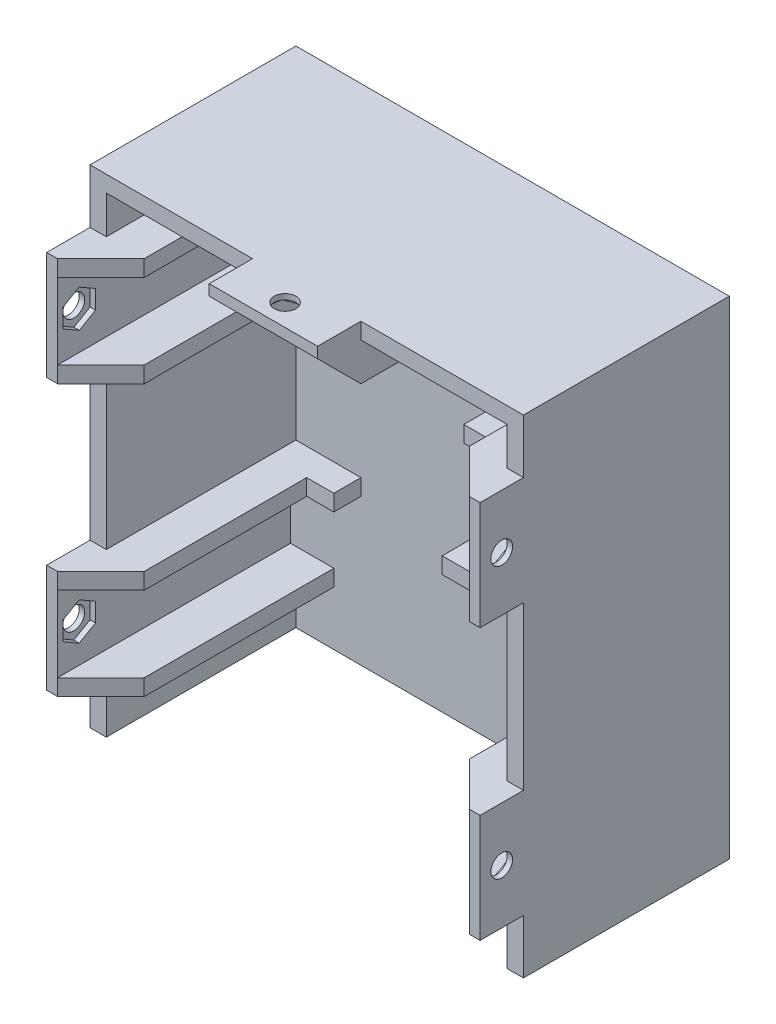
SolidWorks part; units mm, degrees
ref_plane "Front Plane" through (0, 0, 0) normal (0, 0, 1) x (1, 0, 0)
ref_plane "Top Plane" through (0, 0, 0) normal (0, 1, 0) x (1, 0, 0)
ref_plane "Right Plane" through (0, 0, 0) normal (1, 0, 0) x (0, 0, -1)
sketch "Sketch1" plane through (0, 0, 0) normal (0, 0, 1) x (1, 0, 0)
  line L1 (0, 0) -> (80, 0)
  line L2 (0, 0) -> (0, 90)
  line L3 (0, 90) -> (80, 90)
  line L4 (80, 0) -> (80, 90)
  dimension "D1" = 90
  dimension "D2" = 80
extrude "Boss-Extrude1" add sketch "Sketch1" along normal blind 3
sketch "Sketch2" plane through (0, 0, 3) normal (0, 0, 1) x (1, 0, 0)
  line L0 (0, 90) -> (0, 0) construction
  line L1 (0, 80) -> (10, 80)
  line L2 (0, 80) -> (0, 60)
  line L3 (0, 60) -> (10, 60)
  line L4 (10, 80) -> (10, 77)
  line L5 (80, 90) -> (0, 90) construction
  line L6 (10, 77) -> (2, 77)
  line L7 (2, 77) -> (2, 63)
  line L8 (2, 63) -> (10, 63)
  line L9 (10, 63) -> (10, 60)
  dimension "D1" = 10
  dimension "D2" = 20
  dimension "D3" = 3
  dimension "D4" = 3
  dimension "D5" = 2
  dimension "D6" = 10
extrude "Boss-Extrude2" add sketch "Sketch2" along normal blind 8
sketch "Sketch3" plane through (0, 80, 0) normal (0, 1, 0) x (1, 0, 0)
  line L0 (10, -3) -> (2, -11)
  line L1 (10, -11) -> (0, -11) construction
  line L2 (2, -11) -> (10, -11)
  line L3 (10, -11) -> (10, -3)
  line L4 (10, -3) -> (0, -3) construction
  dimension "D1" = 45
extrude "Cut-Extrude1" cut sketch "Sketch3" against normal through all
sketch "Sketch6" plane through (2, 0, 0) normal (1, 0, 0) x (0, 0, -1)
  line L0 (-11, 63) -> (-11, 77) construction
  line L1 (-11, 80) -> (-3, 80) construction
  circle A0 centre (-7, 70) radius 2
  dimension "D1" = 4
  dimension "D2" = 10
extrude "Cut-Extrude3" cut sketch "Sketch6" against normal blind 25
ref_plane "Plane1" through (40, 0, 0) normal (1, 0, 0) x (0, 0, -1)
ref_plane "Plane3" through (0, 45, 0) normal (0, -1, 0) x (-1, 0, 0)
mirror "Mirror4" about plane through (40, 0, 0) normal (1, 0, 0) of "Cut-Extrude3", "Boss-Extrude2", "Cut-Extrude1"
mirror "Mirror5" about plane through (0, 45, 0) normal (0, -1, 0) of "Boss-Extrude2", "Cut-Extrude1", "Mirror4", "Cut-Extrude3"
sketch "Sketch4" plane through (0, 0, 3) normal (0, 0, 1) x (1, 0, 0)
  line L0 (80, 90) -> (0, 90) construction
  line L1 (30, 90) -> (50, 90)
  line L2 (30, 90) -> (30, 80)
  line L3 (30, 80) -> (33, 80)
  line L4 (50, 90) -> (50, 80)
  line L5 (40, -1.65) -> (40, 1.65) construction
  line L6 (33, 80) -> (33, 88)
  line L7 (33, 88) -> (47, 88)
  line L8 (47, 88) -> (47, 80)
  line L9 (47, 80) -> (50, 80)
  dimension "D1" = 20
  dimension "D2" = 10
  dimension "D3" = 10
  dimension "D4" = 3
  dimension "D5" = 3
  dimension "D6" = 2
extrude "Boss-Extrude3" add sketch "Sketch4" along normal blind 8
sketch "Sketch5" plane through (30, 0, 0) normal (-1, 0, 0) x (0, 0, 1)
  line L0 (3, 80) -> (11, 88)
  line L1 (11, 90) -> (11, 80) construction
  line L2 (11, 88) -> (11, 80)
  line L3 (11, 80) -> (3, 80)
  line L4 (3, 90) -> (3, 80) construction
  dimension "D1" = 45
extrude "Cut-Extrude2" cut sketch "Sketch5" against normal blind 25
sketch "Sketch7" plane through (0, 88, 0) normal (0, -1, 0) x (1, 0, 0)
  line L0 (33, 11) -> (47, 11) construction
  line L1 (50, 11) -> (50, 3) construction
  circle A0 centre (40, 7) radius 2
  dimension "D1" = 4
  dimension "D2" = 4
  dimension "D3" = 10
extrude "Cut-Extrude4" cut sketch "Sketch7" against normal blind 25
sketch "Sketch9" plane through (0, 0, 0) normal (0, 0, -1) x (-1, 0, 0)
  line L1 (-80, 90) -> (0, 90)
  line L2 (-80, 90) -> (-80, 0)
  line L3 (-80, 0) -> (0, 0)
  line L4 (0, 90) -> (0, 0)
extrude "Boss-Extrude7" add sketch "Sketch9" along normal blind 35
sketch "Sketch10" plane through (0, 0, 3) normal (0, 0, 1) x (1, 0, 0)
  line L0 (3, 87) -> (30, 87)
  line L1 (30, 90) -> (30, 80) construction
  line L2 (30, 87) -> (30, 80)
  line L3 (30, 80) -> (33, 80)
  line L4 (33, 80) -> (33, 88)
  line L5 (33, 88) -> (47, 88)
  line L6 (47, 88) -> (47, 80)
  line L7 (47, 80) -> (50, 80)
  line L8 (50, 80) -> (50, 87)
  line L9 (50, 80) -> (50, 90) construction
  line L10 (50, 87) -> (77, 87)
  line L11 (77, 87) -> (77, 80)
  line L12 (70, 80) -> (80, 80) construction
  line L13 (77, 80) -> (70, 80)
  line L14 (70, 80) -> (70, 77)
  line L16 (10, 13) -> (10, 10)
  line L17 (10, 30) -> (10, 27)
  line L18 (70, 63) -> (70, 60)
  line L19 (70, 60) -> (70, 63) construction
  line L20 (80, 60) -> (70, 60) construction
  line L21 (70, 60) -> (78.6325, 60)
  line L22 (77, 60) -> (77, 30)
  line L23 (10, 60) -> (10, 63)
  line L24 (3, 60) -> (3, 30)
  line L25 (70, 30) -> (70, 27)
  line L26 (70, 27) -> (78, 27)
  line L27 (78, 27) -> (78, 13)
  line L31 (70, 13) -> (70, 10)
  line L32 (70, 13) -> (70, 10) construction
  line L33 (70, 10) -> (77, 10)
  line L34 (70, 10) -> (80, 10) construction
  line L35 (77, 10) -> (77, 0)
  line L36 (0, 0) -> (80, 0) construction
  line L37 (3, 87) -> (3, 80)
  line L38 (10, 80) -> (0, 80) construction
  line L39 (3, 80) -> (10, 80)
  line L40 (10, 80) -> (10, 77)
  line L41 (10, 77) -> (2, 77)
  line L42 (2, 77) -> (10, 77) construction
  line L43 (2, 77) -> (2, 63)
  line L44 (10, 63) -> (2, 63) construction
  line L45 (2, 63) -> (10, 63)
  line L46 (3, 60) -> (10, 60)
  line L47 (0, 60) -> (10, 60) construction
  line L49 (3, 30) -> (10, 30)
  line L50 (10, 30) -> (10, 27)
  line L51 (10, 27) -> (2, 27)
  line L52 (10, 27) -> (2, 27) construction
  line L53 (2, 27) -> (2, 13)
  line L54 (2, 13) -> (10, 13) construction
  line L55 (2, 13) -> (10, 13)
  line L56 (3, 10) -> (10, 10)
  line L57 (10, 10) -> (0, 10) construction
  line L58 (3, 10) -> (3, 0)
  line L59 (30, 90) -> (0, 90) construction
  line L60 (80, 90) -> (50, 90) construction
  line L61 (80, 80) -> (80, 90) construction
  line L63 (80, 30) -> (80, 60) construction
  line L64 (80, 0) -> (80, 10) construction
  line L65 (0, 10) -> (0, 0) construction
  line L66 (0, 10) -> (0, 30) construction
  line L68 (0, 80) -> (0, 60) construction
  line L69 (0, 90) -> (0, 80) construction
  line L71 (78, 77) -> (78, 63)
  line L72 (80, 80) -> (80, 60) construction
  point P109 (80, 85)
  point P118 (0, 5)
  dimension "D1" = 3
  dimension "D2" = 3
  dimension "D3" = 3
  dimension "D4" = 3
  dimension "D5" = 3
  dimension "D6" = 3
  dimension "D7" = 2
  dimension "D9" = 2
  dimension "D10" = 3
  dimension "D11" = 2
extrude "Cut-Extrude5" cut sketch "Sketch10" against normal blind 35
sketch "Sketch11" plane through (0, 0, -32) normal (0, 0, 1) x (1, 0, 0)
  line L0 (2, 27) -> (2, 13) construction
  line L1 (2, 27) -> (15, 27)
  line L2 (2, 27) -> (2, 30)
  line L3 (2, 30) -> (15, 30)
  line L4 (15, 27) -> (15, 30)
  line L5 (10, 27) -> (2, 27) construction
  line L6 (3, 60) -> (3, 30) construction
  line L7 (3, 50) -> (16, 50)
  line L8 (3, 50) -> (3, 53)
  line L9 (3, 53) -> (16, 53)
  line L10 (16, 50) -> (16, 53)
  line L12 (35, 27) -> (45, 27)
  line L13 (35, 27) -> (35, 30)
  line L14 (35, 30) -> (45, 30)
  line L15 (45, 27) -> (45, 30)
  line L16 (39, 50) -> (46, 50)
  line L17 (39, 50) -> (39, 53)
  line L18 (39, 53) -> (46, 53)
  line L19 (46, 50) -> (46, 53)
  point P23 (16, 51.5)
  dimension "D1" = 13
  dimension "D2" = 3
  dimension "D3" = 20
  dimension "D4" = 13
  dimension "D5" = 3
  dimension "D6" = 20
  dimension "D7" = 23
  dimension "D8" = 20
  dimension "D9" = 3
  dimension "D10" = 7
  dimension "D11" = 10
  dimension "D12" = 3
extrude "Boss-Extrude8" add sketch "Sketch11" along normal blind 5
sketch "Sketch12" plane through (0, 0, -32) normal (0, 0, 1) x (1, 0, 0)
  line L0 (46, 53) -> (39, 53) construction
  line L1 (65, 69) -> (56, 69)
  line L2 (65, 69) -> (65, 58)
  line L3 (65, 58) -> (56, 58)
  line L4 (56, 69) -> (56, 58)
  line L5 (70, 60) -> (70, 63) construction
  point P8 (70, 61.5)
  dimension "D1" = 11
  dimension "D2" = 9
  dimension "D3" = 5
  dimension "D4" = 5
extrude "Cut-Extrude6" cut sketch "Sketch12" against normal blind 46
sketch "Sketch13" plane through (0, 0, -32) normal (0, 0, 1) x (1, 0, 0)
  line L0 (46, 53) -> (39, 53) construction
  line L1 (44.9145, 70) -> (49.9145, 70)
  line L2 (44.9145, 70) -> (44.9145, 58)
  line L3 (44.9145, 58) -> (49.9145, 58)
  line L4 (49.9145, 70) -> (49.9145, 58)
  line L8 (77, 10) -> (70, 10) construction
  dimension "D1" = 5
  dimension "D2" = 12
  dimension "D3" = 5
extrude "Cut-Extrude7" cut sketch "Sketch13" against normal through all
sketch "Sketch14" plane through (0, 88, 0) normal (0, -1, 0) x (1, 0, 0)
  line L1 (43.2079, 5.6926) -> (42.7362, 9.1244)
  line L2 (42.7362, 9.1244) -> (39.5283, 10.4318)
  line L3 (39.5283, 10.4318) -> (36.7921, 8.3074)
  line L4 (36.7921, 8.3074) -> (37.2638, 4.8756)
  line L5 (37.2638, 4.8756) -> (40.4717, 3.5682)
  line L6 (40.4717, 3.5682) -> (43.2079, 5.6926)
  circle A0 centre (40, 7) radius 3 construction
  point P1 (41.1322, 9.7781)
  dimension "D1" = 3
extrude "Cut-Extrude8" cut sketch "Sketch14" against normal blind 1
sketch "Sketch15" plane through (78, 0, 0) normal (-1, 0, 0) x (0, 0, 1)
  line L1 (9.9931, 68.256) -> (10.0069, 71.7201)
  line L2 (10.0069, 71.7201) -> (7.0138, 73.4641)
  line L3 (7.0138, 73.4641) -> (4.0069, 71.744)
  line L4 (4.0069, 71.744) -> (3.9931, 68.2799)
  line L5 (3.9931, 68.2799) -> (6.9862, 66.5359)
  line L6 (6.9862, 66.5359) -> (9.9931, 68.256)
  circle A0 centre (7, 70) radius 3 construction
extrude "Cut-Extrude9" cut sketch "Sketch15" against normal blind 1
mirror "Mirror6" about plane through (40, 0, 0) normal (1, 0, 0) of "Cut-Extrude9"
mirror "Mirror7" about plane through (0, 45, 0) normal (0, -1, 0) of "Mirror6", "Cut-Extrude9"
equation "\"D4@Sketch2\"=\"D3@Sketch2\""
